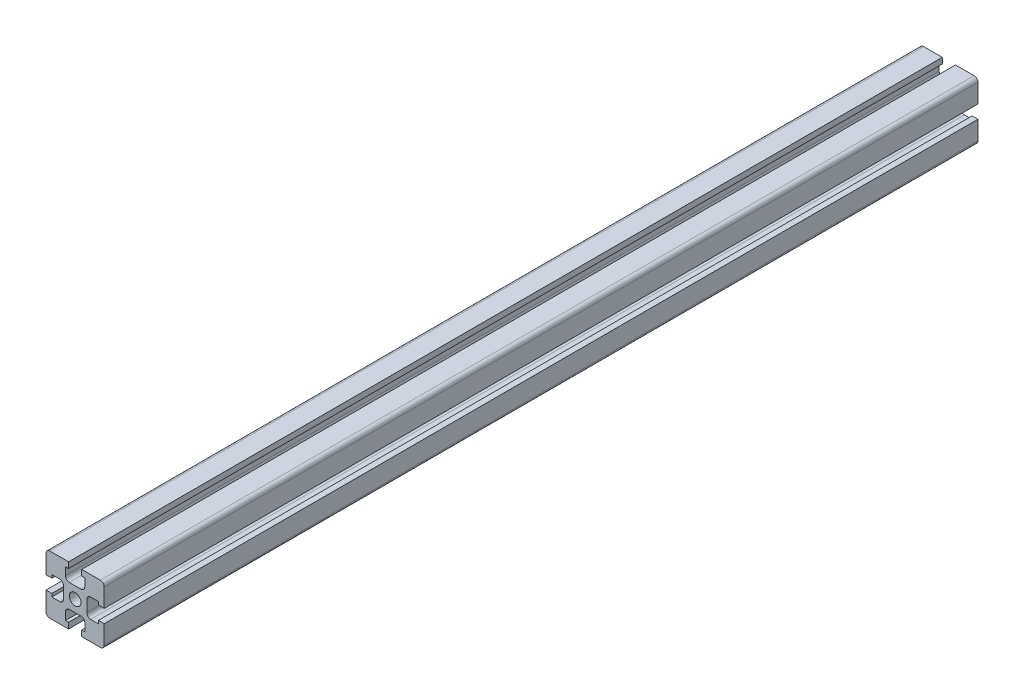
SolidWorks part; units mm, degrees
ref_plane "Front Plane" through (0, 0, 0) normal (0, 0, 1) x (1, 0, 0)
ref_plane "Top Plane" through (0, 0, 0) normal (0, 1, 0) x (1, 0, 0)
ref_plane "Right Plane" through (0, 0, 0) normal (1, 0, 0) x (0, 0, -1)
sketch "Sketch1" plane through (0, 0, 0) normal (0, 0, 1) x (1, 0, 0)
  line L0 (-7.5, 1.7) -> (-7.5, 6.5)
  line L1 (-6.5, 7.5) -> (-1.7, 7.5)
  line L2 (1.7, 7.5) -> (6.5, 7.5)
  line L3 (7.5, 6.5) -> (7.5, 1.7)
  line L4 (7.5, -1.7) -> (7.5, -6.5)
  line L5 (6.5, -7.5) -> (1.7, -7.5)
  line L6 (-1.7, -7.5) -> (-6.5, -7.5)
  line L7 (-7.5, -6.5) -> (-7.5, -1.7)
  line L8 (0, 40.8018) -> (0, -28.0859) construction
  line L9 (0, -37.8882) -> (0, 37.8882) construction
  line L10 (-28.4912, 0) -> (21.8772, 0) construction
  line L11 (27.7026, 0) -> (-27.7026, 0) construction
  line L12 (-1.7, 7.5) -> (-1.7, 6)
  line L13 (-1.7, 6) -> (-2.5, 6)
  line L14 (-2.5, 6) -> (-2.5, 4)
  line L15 (-1.5, 3) -> (0, 3)
  line L16 (0, 3) -> (1.5, 3)
  line L17 (2.5, 4) -> (2.5, 6)
  line L18 (2.5, 6) -> (1.7, 6)
  line L19 (1.7, 6) -> (1.7, 7.5)
  line L20 (-6, -2.5) -> (-4, -2.5)
  line L21 (-4, 2.5) -> (-6, 2.5)
  line L22 (-6, 2.5) -> (-6, 1.7)
  line L23 (-6, -1.7) -> (-6, -2.5)
  line L24 (-7.5, -1.7) -> (-6, -1.7)
  line L25 (-6, 1.7) -> (-7.5, 1.7)
  line L26 (-3, -1.5) -> (-3, 0)
  line L27 (-3, 0) -> (-3, 1.5)
  line L28 (2.5, -6) -> (2.5, -4)
  line L29 (-2.5, -4) -> (-2.5, -6)
  line L30 (-2.5, -6) -> (-1.7, -6)
  line L31 (1.7, -6) -> (2.5, -6)
  line L32 (1.7, -7.5) -> (1.7, -6)
  line L33 (-1.7, -6) -> (-1.7, -7.5)
  line L34 (1.5, -3) -> (0, -3)
  line L35 (0, -3) -> (-1.5, -3)
  line L36 (6, 2.5) -> (4, 2.5)
  line L37 (4, -2.5) -> (6, -2.5)
  line L38 (6, -2.5) -> (6, -1.7)
  line L39 (6, 1.7) -> (6, 2.5)
  line L40 (7.5, 1.7) -> (6, 1.7)
  line L41 (6, -1.7) -> (7.5, -1.7)
  line L42 (3, 1.5) -> (3, 0)
  line L43 (3, 0) -> (3, -1.5)
  arc A0 (4, -2.5) -> (3, -1.5) centre (4, -1.5) cw
  arc A1 (4, 2.5) -> (3, 1.5) centre (4, 1.5) ccw
  arc A2 (1.5, 3) -> (2.5, 4) centre (1.5, 4) ccw
  arc A3 (-2.5, 4) -> (-1.5, 3) centre (-1.5, 4) ccw
  arc A4 (-4, 2.5) -> (-3, 1.5) centre (-4, 1.5) cw
  arc A5 (-4, -2.5) -> (-3, -1.5) centre (-4, -1.5) ccw
  arc A6 (2.5, -4) -> (1.5, -3) centre (1.5, -4) ccw
  arc A7 (-2.5, -4) -> (-1.5, -3) centre (-1.5, -4) cw
  arc A8 (-6.5, -7.5) -> (-7.5, -6.5) centre (-6.5, -6.5) cw
  arc A9 (7.5, -6.5) -> (6.5, -7.5) centre (6.5, -6.5) cw
  arc A10 (6.5, 7.5) -> (7.5, 6.5) centre (6.5, 6.5) cw
  arc A11 (-7.5, 6.5) -> (-6.5, 7.5) centre (-6.5, 6.5) cw
  circle A12 centre (0, 0) radius 1.5
  point P58 (0, 0)
  point P79 (-7.5, 7.5)
  dimension "D8" = 1
  dimension "D9" = 3
  dimension "D1" = 15
  dimension "D2" = 5.8
  dimension "D3" = 15
  dimension "D4" = 1.5
  dimension "D6" = 6
  dimension "D7" = 5
  dimension "D5" = 4
extrude "Boss-Extrude1" add sketch "Sketch1" along normal mid plane 225 contours A11 L0 L25 L22 L21 A4 L27 L26 A5 L20 L23 L24 L7 A8 L6 L33 L30 L29 A7 L35 L34 A6 L28 L31 L32 L5 A9 L4 L41 L38 L37 A0 L43 L42 A1 L36 L39 L40 L3 A10 L2 L19 L18 L17 A2 L16 L15 A3 L14 L13 L12
